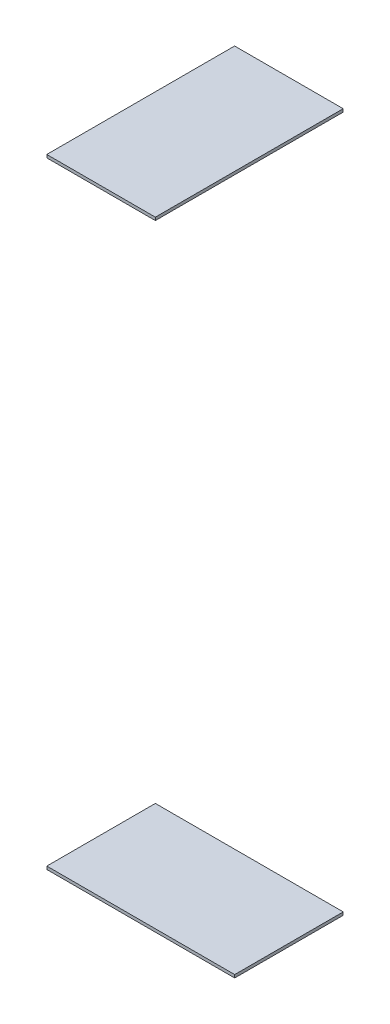
SolidWorks part; units mm, degrees
ref_plane "Front Plane" through (0, 0, 0) normal (0, 0, 1) x (1, 0, 0)
ref_plane "Top Plane" through (0, 0, 0) normal (0, 1, 0) x (1, 0, 0)
ref_plane "Right Plane" through (0, 0, 0) normal (1, 0, 0) x (0, 0, -1)
sketch "Sketch2" plane through (0, 0, 0) normal (0, 0, 1) x (1, 0, 0)
  line L1 (100.0226, 0) -> (0, 0)
  line L2 (100.0226, 0) -> (100.0226, 1.5875)
  line L3 (100.0226, 1.5875) -> (0, 1.5875)
  line L4 (0, 0) -> (0, 1.5875)
extrude "Boss-Extrude1" add sketch "Sketch2" along normal blind 150
sketch "Sketch3" plane through (0, 0, 0) normal (0, -1, 0) x (1, 0, 0)
  line L0 (100.0226, 57.7789) -> (0, 57.7789)
  line L1 (100.0226, 57.7789) -> (100.0226, 150)
  line L2 (0, 57.7789) -> (0, 150)
  line L3 (100.0226, 150) -> (0, 150)
  line L4 (383.5953, -225.7938) -> (2.8537, 154.9478) construction
  line L5 (100.0226, 150) -> (100.0226, 0) construction
  line L6 (0, 150) -> (0, 0) construction
extrude "Cut-Extrude1" cut sketch "Sketch3" against normal blind 1.5875
sketch "Sketch4" plane through (-128.6475, 0, 0) normal (-1, 0, 0) x (0, 0, 1)
  line L1 (-228.6475, 141.639) -> (-128.6475, 141.639)
  line L2 (-228.6475, 141.639) -> (-228.6475, 143.2265)
  line L3 (-228.6475, 143.2265) -> (-128.6475, 143.2265)
  line L4 (-128.6475, 141.639) -> (-128.6475, 143.2265)
extrude "Boss-Extrude2" add sketch "Sketch4" along normal blind 100 separate body
sketch "Sketch5" plane through (0, 141.639, 0) normal (0, -1, 0) x (1, 0, 0)
  line L0 (-186.449, -228.6475) -> (-228.6475, -228.6475)
  line L1 (-186.449, -228.6475) -> (-186.449, -128.6475)
  line L2 (-228.6475, -228.6475) -> (-228.6475, -128.6475)
  line L3 (-186.449, -128.6475) -> (-228.6475, -128.6475)
  line L4 (-283.5953, -131.5012) -> (97.1463, -512.2428) construction
  line L5 (-228.6475, -228.6475) -> (-128.6475, -228.6475) construction
  line L6 (-228.6475, -128.6475) -> (-128.6475, -128.6475) construction
extrude "Cut-Extrude2" cut sketch "Sketch5" against normal blind 1.5875
